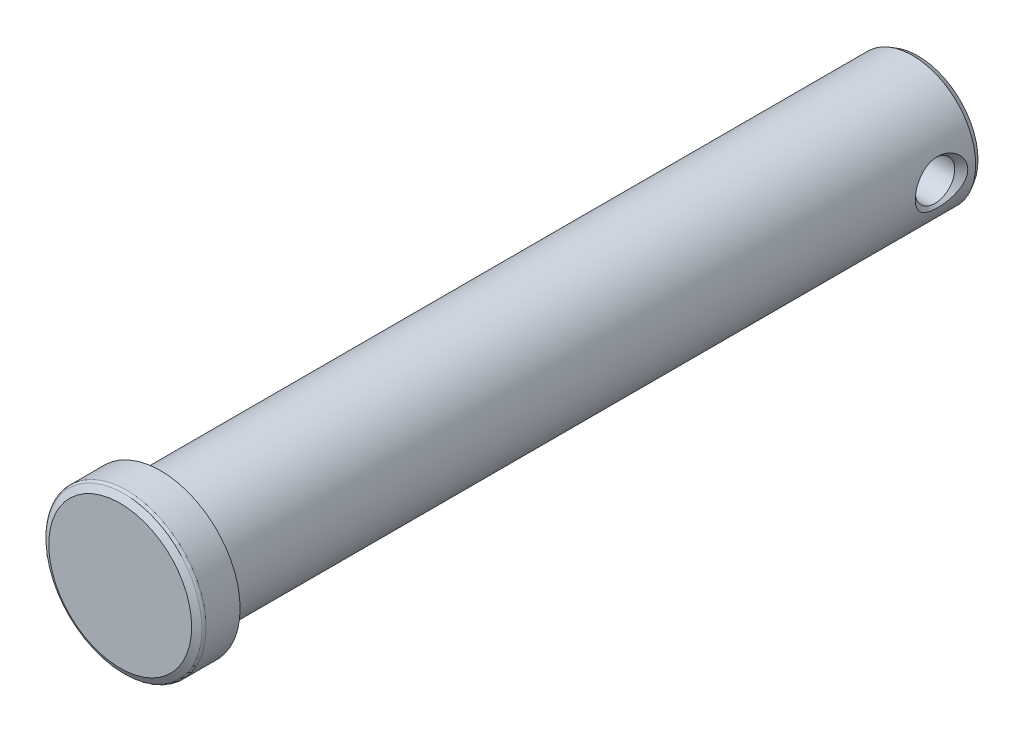
SolidWorks part; units mm, degrees
ref_plane "Front" through (0, 0, 0) normal (0, 0, 1) x (1, 0, 0)
ref_plane "Top" through (0, 0, 0) normal (0, 1, 0) x (1, 0, 0)
ref_plane "Right" through (0, 0, 0) normal (1, 0, 0) x (0, 0, -1)
sketch "Sketch1" plane through (0, 0, 0) normal (1, 0, 0) x (0, 0, -1)
  line L0 (-42.164, 0) -> (-38.1, 0) construction
  line L1 (-38.1, 0) -> (38.1, 0) construction
  line L2 (-42.164, 0) -> (-42.164, 7.1882)
  line L3 (-42.164, 7.1882) -> (-41.6947, 8.001)
  line L4 (-41.6947, 8.001) -> (-38.1, 8.001)
  line L5 (-38.1, 8.001) -> (-38.1, 6.35)
  line L6 (-38.1, 6.35) -> (37.5501, 6.35)
  line L7 (37.5501, 6.35) -> (38.1, 6.0325)
  line L8 (38.1, 6.0325) -> (38.1, 0)
  line L9 (-38.1, -6.35) -> (-38.1, -8.001)
  circle A0 centre (34.1122, 0) radius 1.9812
  point P4 (0, 0)
  point P17 (32.131, 0)
  dimension "Through Hole Diameter" = 3.9624
  dimension "Diameter" = 12.7
  dimension "D1" = 30
  dimension "D2" = 0.3175
  dimension "Head Height" = 4.064
  dimension "Head Diameter" = 16.002
  dimension "D5" = 0.8128
  dimension "Length" = 76.2
  dimension "Usable Length" = 70.231
sketch "Sketch2" plane through (0, 0, 0) normal (1, 0, 0) x (0, 0, -1)
  line L0 (38.1, 6.0325) -> (38.1, 0) construction
  line L1 (37.5501, 6.35) -> (38.1, 6.0325) construction
  line L2 (-38.1, 6.35) -> (37.5501, 6.35) construction
  line L3 (-38.1, 8.001) -> (-38.1, 6.35) construction
  line L4 (-41.6947, 8.001) -> (-38.1, 8.001) construction
  line L5 (-42.164, 7.1882) -> (-41.6947, 8.001) construction
  line L6 (-42.164, 0) -> (-42.164, 7.1882) construction
  line L7 (38.1, 6.0325) -> (38.1, 0)
  line L8 (37.5501, 6.35) -> (38.1, 6.0325)
  line L9 (-38.1, 6.35) -> (37.5501, 6.35)
  line L10 (-38.1, 8.001) -> (-38.1, 6.35)
  line L11 (-41.6947, 8.001) -> (-38.1, 8.001)
  line L12 (-42.164, 7.1882) -> (-41.6947, 8.001)
  line L13 (-42.164, 0) -> (-42.164, 7.1882)
  line L14 (-42.164, 0) -> (38.1, 0)
revolve "Revolve1" add sketch "Sketch2" angle 360 about L1
sketch "Sketch3" plane through (0, 0, 0) normal (1, 0, 0) x (0, 0, -1)
  circle A0 centre (34.1122, 0) radius 1.9812 construction
  circle A1 centre (34.1122, 0) radius 1.9812
extrude "Cut-Extrude1" cut sketch "Sketch3" against normal through all both and the other way through all
fillet "Fillet1" radius 0.3175 2 edges at (6.35, 0, 38.1) (8.001, 0, 41.6947)
sketch "Sketch4" plane through (0, 0, 0) normal (0, 1, 0) x (1, 0, 0)
  line L0 (6.35, 34.1122) -> (-6.35, 34.1122) construction
  line L1 (6.35, 34.1122) -> (6.35, 31.4706)
  line L2 (6.35, 31.4706) -> (3.7084, 34.1122)
  line L3 (6.35, -37.7825) -> (6.35, 32.131) construction
  line L4 (0, 34.1122) -> (0, 0) construction
  line L5 (-6.35, 31.4706) -> (-3.7084, 34.1122)
  line L6 (-6.35, 34.1122) -> (-6.35, 31.4706)
  line L7 (-6.35, 34.1122) -> (-3.7084, 34.1122)
  line L8 (3.7084, 34.1122) -> (6.35, 34.1122)
  dimension "D1" = 45
  dimension "D2" = 5.2832
revolve "Cut-Revolve1" cut sketch "Sketch4" angle 360 about L0
equation "\"D2@Sketch1\"=\"Diameter@Sketch1\" * .025"
equation "\"D5@Sketch1\" = \"Head Height@Sketch1\" * .2"
equation "\"D1@Fillet1\"=\"D2@Sketch1\""
equation "\"D2@Sketch4\"=\"Through Hole Diameter@Sketch1\" * 4/3"
